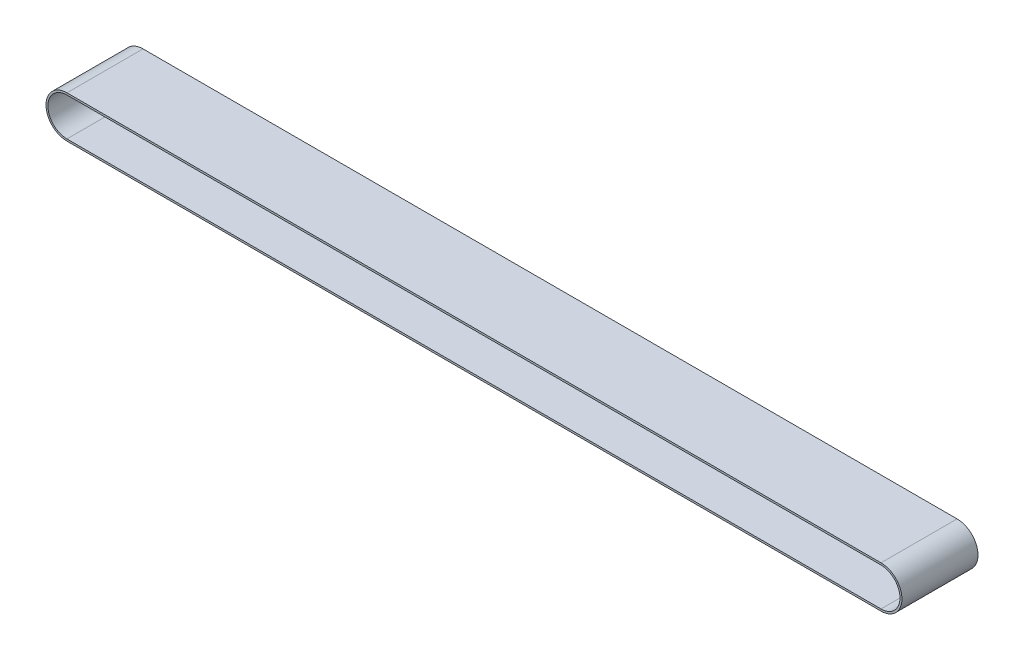
SolidWorks part; units mm, degrees
ref_plane "Front Plane" through (0, 0, 0) normal (0, 0, 1) x (1, 0, 0)
ref_plane "Top Plane" through (0, 0, 0) normal (0, 1, 0) x (1, 0, 0)
ref_plane "Right Plane" through (0, 0, 0) normal (1, 0, 0) x (0, 0, -1)
sketch "Sketch1" plane through (0, 0, 0) normal (0, 0, 1) x (1, 0, 0)
  line L0 (-383, 20) -> (473, 20)
  line L1 (-383, -20) -> (473, -20)
  line L2 (-383, 22) -> (473, 22)
  line L3 (473, -22) -> (-383, -22)
  arc A2 (-383, -20) -> (-383, 20) centre (-383, 0) cw
  arc A3 (473, -20) -> (473, 20) centre (473, 0) ccw
  arc A6 (-383, -22) -> (-383, 22) centre (-383, 0) cw
  arc A7 (473, 22) -> (473, -22) centre (473, 0) cw
  dimension "D3" = 20
  dimension "D1" = 856
  dimension "D2" = 22
extrude "Boss-Extrude1" add sketch "Sketch1" along normal blind 80
